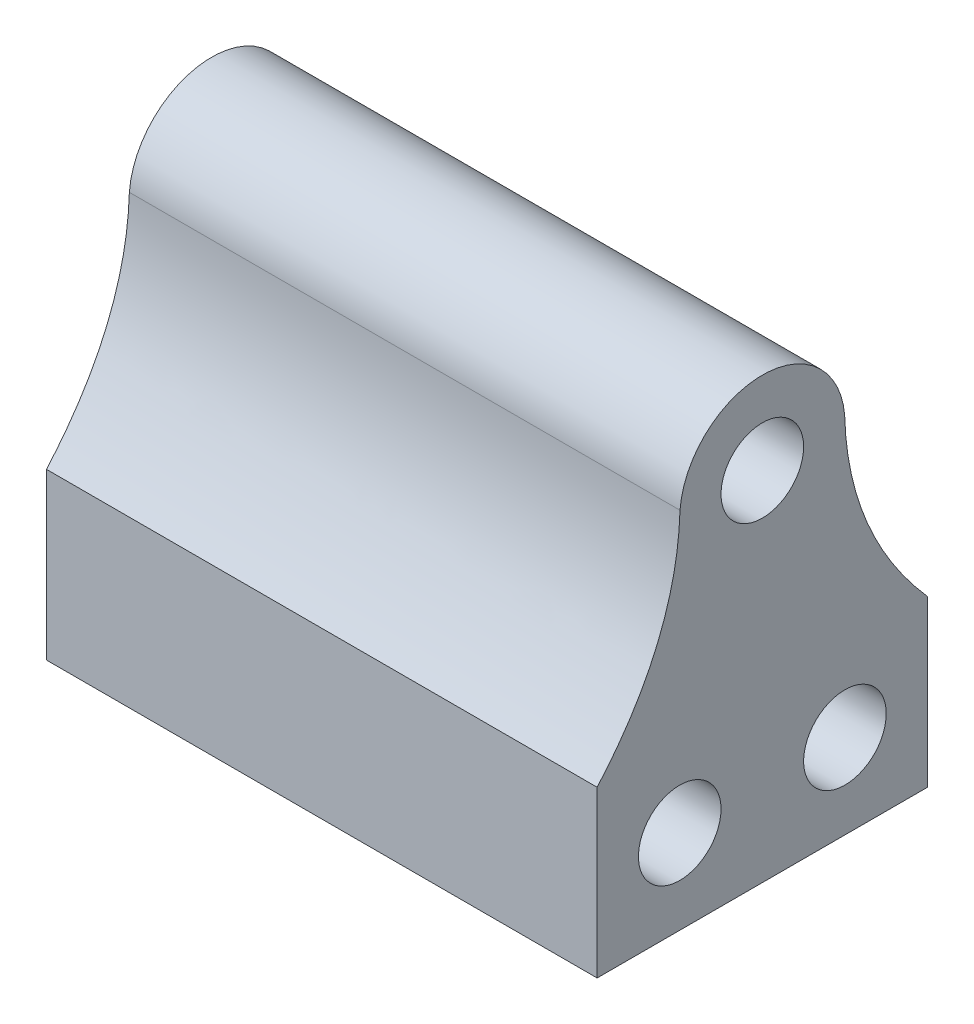
SolidWorks part; units mm, degrees
ref_plane "Front Plane" through (0, 0, 0) normal (0, 0, 1) x (1, 0, 0)
ref_plane "Top Plane" through (0, 0, 0) normal (0, 1, 0) x (1, 0, 0)
ref_plane "Right Plane" through (0, 0, 0) normal (1, 0, 0) x (0, 0, -1)
sketch "Sketch1" plane through (0, 0, 0) normal (0, 1, 0) x (1, 0, 0)
  line L1 (-50, 30) -> (50, 30)
  line L2 (-50, 30) -> (-50, -30)
  line L3 (-50, -30) -> (50, -30)
  line L4 (50, 30) -> (50, -30)
  dimension "D1" = 100
  dimension "D2" = 60
  dimension "D3" = 30
  dimension "D4" = 50
extrude "Boss-Extrude1" add sketch "Sketch1" along normal blind 30
sketch "Sketch2" plane through (50, 0, 0) normal (1, 0, 0) x (0, 0, -1)
  line L0 (-30, 30) -> (30, 30)
  arc A0 (14.955, 65.9848) -> (-14.9502, 66.0446) centre (0, 64.8233) ccw
  spline S0 degree 2 poles (-30, 30) (-15.5307, 46.4421) (-14.9502, 66.0446) knots 0 0 0 1 1 1
  spline S1 degree 2 poles (30, 30) (15.5046, 46.413) (14.955, 65.9848) knots 0 0 0 1 1 1
  point P1 (0, 0)
  point P7 (-15, 65.944)
  point P10 (0, 0)
  dimension "D1" = 30
  dimension "D2" = 30
extrude "Boss-Extrude2" add sketch "Sketch2" against normal blind 100
sketch "Sketch4" plane through (50, 0, 0) normal (1, 0, 0) x (0, 0, -1)
  circle A0 centre (0, 64.8233) radius 7.5
  arc A1 (14.955, 65.9848) -> (-14.9502, 66.0446) centre (0, 64.8233) ccw construction
  circle A2 centre (-15, 15.3369) radius 7.5
  circle A3 centre (15, 15.3369) radius 7.5
  dimension "D1" = 0
  dimension "D2" = 15
  dimension "D5" = 15
  dimension "D6" = 15
  dimension "D3" = 15
  dimension "D4" = 15
extrude "Cut-Extrude1" cut sketch "Sketch4" against normal blind 100
